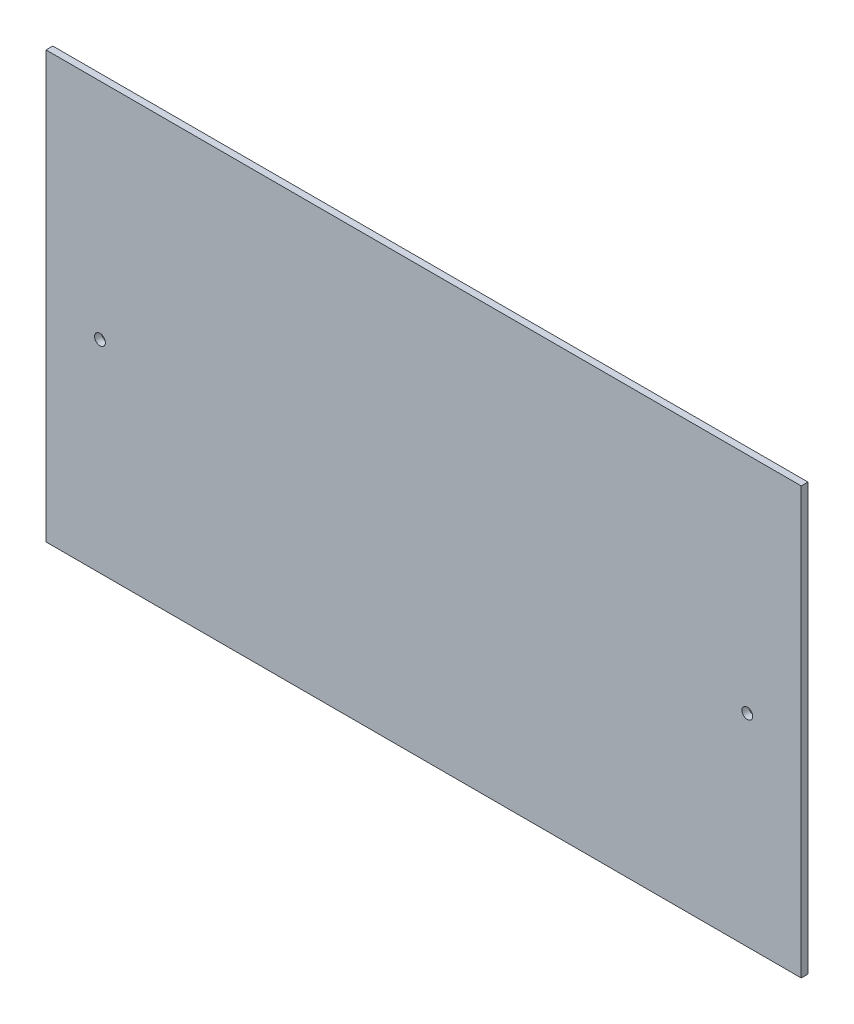
SolidWorks part; units mm, degrees
material "Acrilico (impatto medio-alto)"
ref_plane "Piano frontale" through (0, 0, 0) normal (0, 0, 1) x (1, 0, 0)
ref_plane "Piano superiore" through (0, 0, 0) normal (0, 1, 0) x (1, 0, 0)
ref_plane "Piano destro" through (0, 0, 0) normal (1, 0, 0) x (0, 0, -1)
sketch "Schizzo1" plane through (0, 0, 0) normal (0, 0, 1) x (1, 0, 0)
  line L1 (0, 0) -> (280, 0)
  line L3 (0, 158) -> (280, 158)
  line L14 (0, 0) -> (0, 158)
  line L15 (280, 0) -> (280, 158)
  dimension "D1" = 158
  dimension "D2" = 280
extrude "Estrusione-Estrusione1" add sketch "Schizzo1" along normal blind 2.5
sketch "Schizzo2" plane through (0, 0, 2.5) normal (0, 0, 1) x (1, 0, 0)
  circle A0 centre (260, 75) radius 2
  circle A1 centre (20, 75) radius 2
  dimension "D1" = 4
extrude "Taglio-Estrusione1" cut sketch "Schizzo2" against normal blind 10
